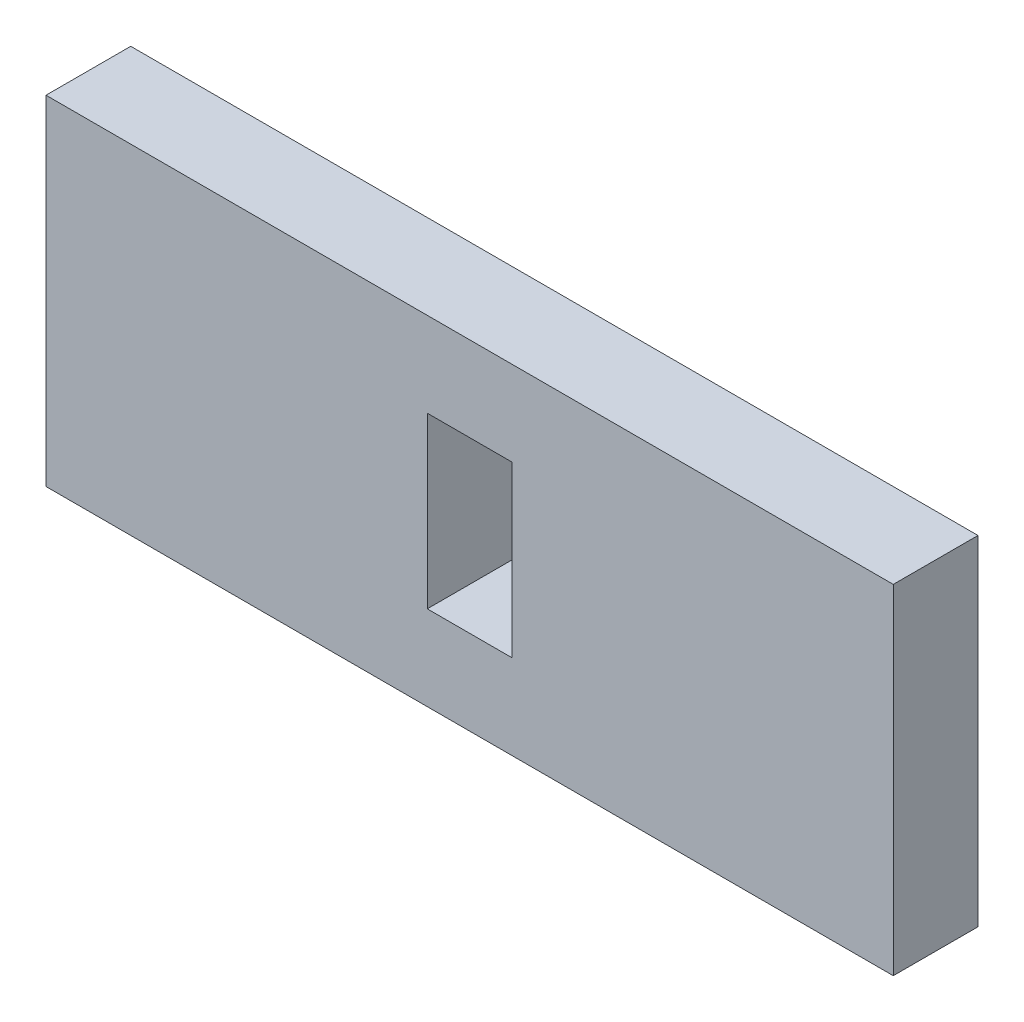
SolidWorks part; units mm, degrees
ref_plane "Front Plane" through (0, 0, 0) normal (0, 0, 1) x (1, 0, 0)
ref_plane "Top Plane" through (0, 0, 0) normal (0, 1, 0) x (1, 0, 0)
ref_plane "Right Plane" through (0, 0, 0) normal (1, 0, 0) x (0, 0, -1)
sketch "Esquisse1" plane through (0, 0, 0) normal (0, 0, 1) x (1, 0, 0)
  line L1 (0, 0) -> (-50, 0)
  line L2 (0, 0) -> (0, -20)
  line L3 (0, -20) -> (-50, -20)
  line L4 (-50, 0) -> (-50, -20)
  line L5 (-25, -20) -> (-25, 0) construction
  line L6 (0, -10) -> (-50, -10) construction
  line L7 (-27.5, -15) -> (-22.5, -15)
  line L8 (-27.5, -15) -> (-27.5, -5)
  line L9 (-27.5, -5) -> (-22.5, -5)
  line L10 (-22.5, -15) -> (-22.5, -5)
  line L11 (-27.5, -15) -> (-22.5, -5) construction
  line L12 (-27.5, -5) -> (-22.5, -15) construction
  point P4 (-25, -10)
  point P212 (-25, -10)
  dimension "D1" = 20
  dimension "D2" = 50
  dimension "D3" = 5
  dimension "D4" = 10
extrude "Boss.-Extru.1" add sketch "Esquisse1" along normal blind 5
